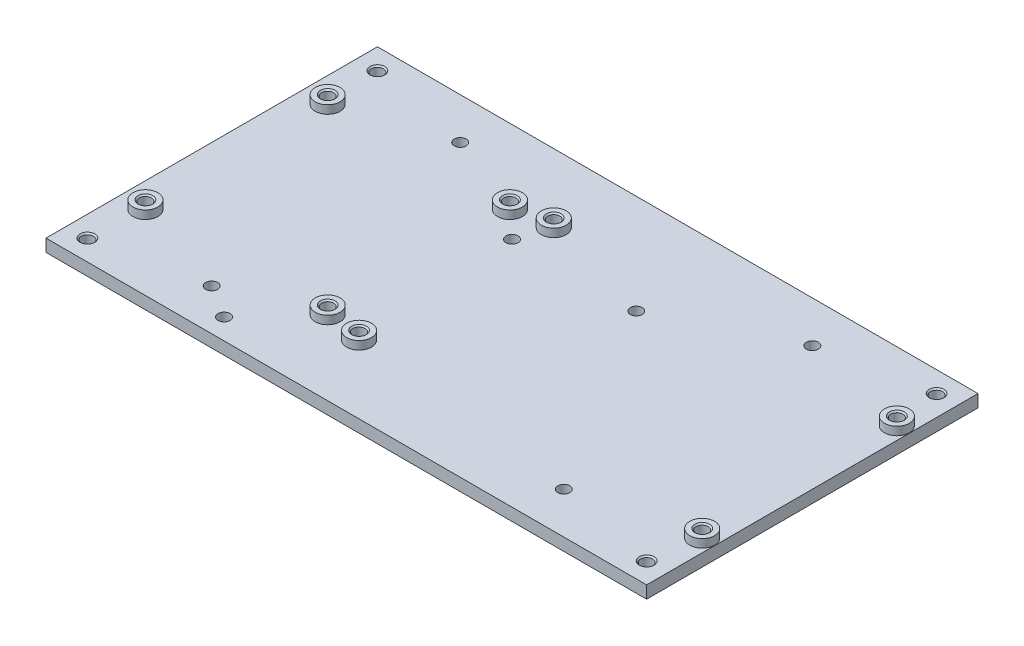
SolidWorks part; units mm, degrees
ref_plane "前视基准面" through (0, 0, 0) normal (0, 0, 1) x (1, 0, 0)
ref_plane "上视基准面" through (0, 0, 0) normal (0, 1, 0) x (1, 0, 0)
ref_plane "右视基准面" through (0, 0, 0) normal (1, 0, 0) x (0, 0, -1)
other "Configuration Table"
sketch "草图1" plane through (0, 0, 0) normal (0, 1, 0) x (1, 0, 0)
  line L0 (145, 80) -> (56, 80) construction
  line L1 (0, 0) -> (145, 0)
  line L2 (0, 0) -> (0, 80)
  line L3 (0, 80) -> (145, 80)
  line L4 (145, 0) -> (145, 80)
  line L5 (56, 80) -> (56, 0) construction
  dimension "D1" = 145
  dimension "D2" = 80
extrude "凸台-拉伸1" add sketch "草图1" along normal blind 3
sketch "草图3" plane through (0, 3, 0) normal (0, 1, 0) x (1, 0, 0)
  line L0 (145, 80) -> (56, 80) construction
  line L1 (145, 80) -> (0, 80) construction
  line L2 (56, 80) -> (56, 0) construction
  line L3 (0, 0) -> (145, 0) construction
  line L4 (56, 80) -> (59.085, 80) construction
  line L5 (59.085, 80) -> (59.085, 63.5) construction
  line L6 (0, 80) -> (6, 80) construction
  line L7 (56, 40) -> (145, 40) construction
  line L8 (145, 0) -> (145, 80) construction
  line L9 (100.5, 80) -> (100.5, 0) construction
  line L10 (6, 80) -> (6, 62) construction
  line L11 (0, 40) -> (56, 40) construction
  line L12 (0, 80) -> (0, 0) construction
  line L13 (28, 30) -> (28, 60) construction
  circle A0 centre (59.085, 63.5) radius 3
  circle A1 centre (59.085, 16.5) radius 3
  circle A2 centre (141.915, 16.5) radius 3
  circle A3 centre (141.915, 63.5) radius 3
  circle A4 centre (6, 62) radius 3
  circle A5 centre (50, 62) radius 3
  circle A6 centre (6, 18) radius 3
  circle A7 centre (50, 18) radius 3
  dimension "D4" = 6
  dimension "D1" = 89
  dimension "D2" = 3.085
  dimension "D3" = 16.5
  dimension "D5" = 6
  dimension "D6" = 18
extrude "凸台-拉伸2" add sketch "草图3" along normal blind 2
sketch "草图7" plane through (0, 5, 0) normal (0, 1, 0) x (1, 0, 0)
  line L0 (0, 40) -> (145, 40) construction
  line L1 (0, 80) -> (0, 0) construction
  line L2 (145, 0) -> (145, 80) construction
  line L3 (50, 62) -> (6, 62) construction
  line L4 (28, 62) -> (28, 0) construction
  line L5 (0, 0) -> (145, 0) construction
  line L6 (59.085, 63.5) -> (141.915, 63.5) construction
  line L7 (100.5, 63.5) -> (100.5, 0) construction
  circle A0 centre (6, 62) radius 1.75
  circle A1 centre (50, 62) radius 1.75
  circle A2 centre (50, 18) radius 1.75
  circle A3 centre (6, 18) radius 1.75
  circle A4 centre (59.085, 63.5) radius 1.75
  circle A5 centre (141.915, 63.5) radius 1.75
  circle A6 centre (141.915, 16.5) radius 1.75
  circle A7 centre (59.085, 16.5) radius 1.75
  point P0 (6, 62)
  point P9 (50, 62)
  point P15 (59.085, 63.5)
  point P16 (141.915, 63.5)
  point P22 (50, 18)
  point P24 (6, 18)
  point P28 (141.915, 16.5)
  point P30 (59.085, 16.5)
  point P49 (6, 62)
  point P51 (50, 62)
  point P53 (59.085, 63.5)
  point P54 (6, 62)
  point P56 (50, 62)
  point P58 (59.085, 63.5)
  point P60 (141.915, 63.5)
hole_wizard "M3.5 螺纹孔4" positions "草图7" profile "草图9" tap size "M3.5" standard "GB"
sketch "草图9" plane through (141.915, 5, -63.5) normal (1, 0, 0) x (0, 0, 1)
  line L0 (0, 0) -> (0, 12.0712)
  line L1 (0, 12.0712) -> (1.45, 11.2)
  line L2 (1.45, 11.2) -> (1.45, 0.325)
  line L3 (1.45, 0.325) -> (1.775, 0)
  line L5 (1.775, 0) -> (0, 0)
  line L6 (-1.45, 0.325) -> (-1.775, 0) construction
  line L10 (0, 12.0712) -> (-1.45, 11.2) construction
  line L11 (0, -6.35) -> (0, 107.95) construction
  dimension "螺纹孔钻头直径" = 2.9
  dimension "螺纹孔钻头深度" = 11.2
  dimension "近端锥形沉头孔直径" = 3.55
  dimension "近端锥形沉头孔角度" = 90
  dimension "导头角度" = 118
cosmetic thread "孔螺蚊线23" parameters "D1"=9.4, "D2"=3.5
cosmetic thread "孔螺蚊线27" parameters "D1"=9.4, "D2"=3.5
cosmetic thread "孔螺蚊线28" parameters "D1"=9.4, "D2"=3.5
cosmetic thread "孔螺蚊线29" parameters "D1"=9.4, "D2"=3.5
cosmetic thread "孔螺蚊线30" parameters "D1"=9.4, "D2"=3.5
cosmetic thread "孔螺蚊线31" parameters "D1"=9.4, "D2"=3.5
cosmetic thread "孔螺蚊线32" parameters "D1"=9.4, "D2"=3.5
cosmetic thread "孔螺蚊线33" parameters "D1"=9.4, "D2"=3.5
sketch "草图10" plane through (0, 0, 0) normal (0, -1, 0) x (1, 0, 0)
  line L0 (0, 0) -> (145, 0) construction
  line L1 (0, 0) -> (18.5, 0) construction
  line L5 (72.5, 0) -> (72.5, -80) construction
  line L6 (145, -80) -> (0, -80) construction
  line L7 (18.5, 0) -> (18.5, -10) construction
  line L8 (145, 0) -> (126.5, 0) construction
  line L9 (126.5, 0) -> (126.5, -10) construction
  line L10 (145, -80) -> (126.5, -80) construction
  line L11 (126.5, -80) -> (126.5, -70) construction
  line L12 (18.5, -10) -> (18.5, -14.75) construction
  line L13 (18.5, -10) -> (126.5, -10) construction
  line L14 (18.5, -10) -> (18.5, -14.75) construction
  line L16 (126.5, -10) -> (126.5, -70) construction
  line L17 (18.5, -10) -> (20, -10) construction
  line L18 (0, 0) -> (38, 0) construction
  line L20 (38, 0) -> (38, -10) construction
  line L22 (0, -80) -> (30, -80) construction
  line L25 (30, -10) -> (30, -11.75) construction
  line L31 (38, -65.7538) -> (38, -66) construction
  line L35 (30, -10) -> (30, -56) construction
  line L37 (30, -56) -> (56.5, -56) construction
  line L39 (56.5, -56) -> (86.5, -56) construction
  circle A4 centre (115, -10) radius 1.75
  circle A5 centre (30, -10) radius 1.75
  circle A6 centre (56.5, -56) radius 1.75
  circle A7 centre (86.5, -56) radius 1.75
  point P22 (38, -5)
  point P27 (107, -5)
  point P29 (107, -60)
  point P31 (38, -60)
  point P58 (30, -70)
  point P61 (115, -70)
  point P63 (115, -10)
  point P65 (30, -10)
  point P100 (56.5, -56)
  point P107 (86.5, -56)
  point P119 (56.5, -56)
  point P121 (86.5, -56)
  dimension "D5" = 46
  dimension "D7" = 20
  dimension "D9" = 30
  dimension "D1" = 18.5
  dimension "D2" = 10
  dimension "D3" = 4.75
  dimension "D4" = 38
  dimension "D6" = 30
  dimension "D8" = 26.5
hole_wizard "M3.5 螺纹孔5" positions "草图10" profile "草图12" tap size "M3.5" standard "GB"
sketch "草图12" plane through (86.5, 0, -56) normal (1, 0, 0) x (0, 0, -1)
  line L0 (0, 0) -> (0, 7.8712)
  line L1 (0, 7.8712) -> (1.45, 7)
  line L2 (1.45, 7) -> (1.45, 0.325)
  line L3 (1.45, 0.325) -> (1.775, 0)
  line L5 (1.775, 0) -> (0, 0)
  line L6 (-1.45, 0.325) -> (-1.775, 0) construction
  line L10 (0, 7.8712) -> (-1.45, 7) construction
  line L11 (0, -6.35) -> (0, 107.95) construction
  dimension "螺纹孔钻头直径" = 2.9
  dimension "螺纹孔钻头深度" = 7
  dimension "近端锥形沉头孔直径" = 3.55
  dimension "近端锥形沉头孔角度" = 90
  dimension "导头角度" = 118
cosmetic thread "孔螺蚊线36" parameters "D1"=4.4, "D2"=3.5
cosmetic thread "孔螺蚊线42" parameters "D1"=4.4, "D2"=3.5
cosmetic thread "孔螺蚊线43" parameters "D1"=4.4, "D2"=3.5
cosmetic thread "孔螺蚊线45" parameters "D1"=4.4, "D2"=3.5
cosmetic thread "孔螺蚊线53" parameters "D1"=4.4, "D2"=3.5
cosmetic thread "孔螺蚊线54" parameters "D1"=4.4, "D2"=3.5
cosmetic thread "孔螺蚊线55" parameters "D1"=4.4, "D2"=3.5
sketch "草图13" plane through (0, 3, 0) normal (0, 1, 0) x (1, 0, 0)
  line L0 (0, 80) -> (5, 80) construction
  line L1 (145, 80) -> (0, 80) construction
  line L2 (5, 80) -> (5, 75) construction
  line L3 (72.5, 80) -> (72.5, 0) construction
  line L4 (0, 0) -> (145, 0) construction
  line L5 (0, 40) -> (145, 40) construction
  line L6 (0, 80) -> (0, 0) construction
  line L7 (145, 0) -> (145, 80) construction
  circle A0 centre (5, 75) radius 1.75
  circle A1 centre (140, 75) radius 1.75
  circle A2 centre (140, 5) radius 1.75
  circle A3 centre (5, 5) radius 1.75
  point P6 (5, 75)
  point P17 (140, 75)
  point P19 (140, 5)
  point P21 (5, 5)
  point P25 (5, 75)
  dimension "D1" = 5
  dimension "D2" = 5
hole_wizard "M3.5 螺纹孔7" positions "草图13" profile "草图15" tap size "M3.5" standard "GB" end condition through all
sketch "草图15" plane through (5, 3, -75) normal (1, 0, 0) x (0, 0, 1)
  line L0 (0, 0) -> (0, 3)
  line L1 (0, 3) -> (1.45, 3)
  line L2 (1.45, 3) -> (1.45, 0.325)
  line L3 (1.45, 0.325) -> (1.775, 0)
  line L5 (1.775, 0) -> (0, 0)
  line L6 (-1.45, 0.325) -> (-1.775, 0) construction
  line L11 (0, -6.35) -> (0, 107.95) construction
  dimension "通孔螺纹孔钻头直径" = 2.9
  dimension "通孔螺纹孔钻头深度" = 3
  dimension "近端锥形沉头孔直径" = 3.55
  dimension "近端锥形沉头孔角度" = 90
cosmetic thread "孔螺蚊线49" parameters "D2"=3.5
cosmetic thread "孔螺蚊线50" parameters "D2"=3.5
cosmetic thread "孔螺蚊线51" parameters "D2"=3.5
cosmetic thread "孔螺蚊线52" parameters "D2"=3.5
